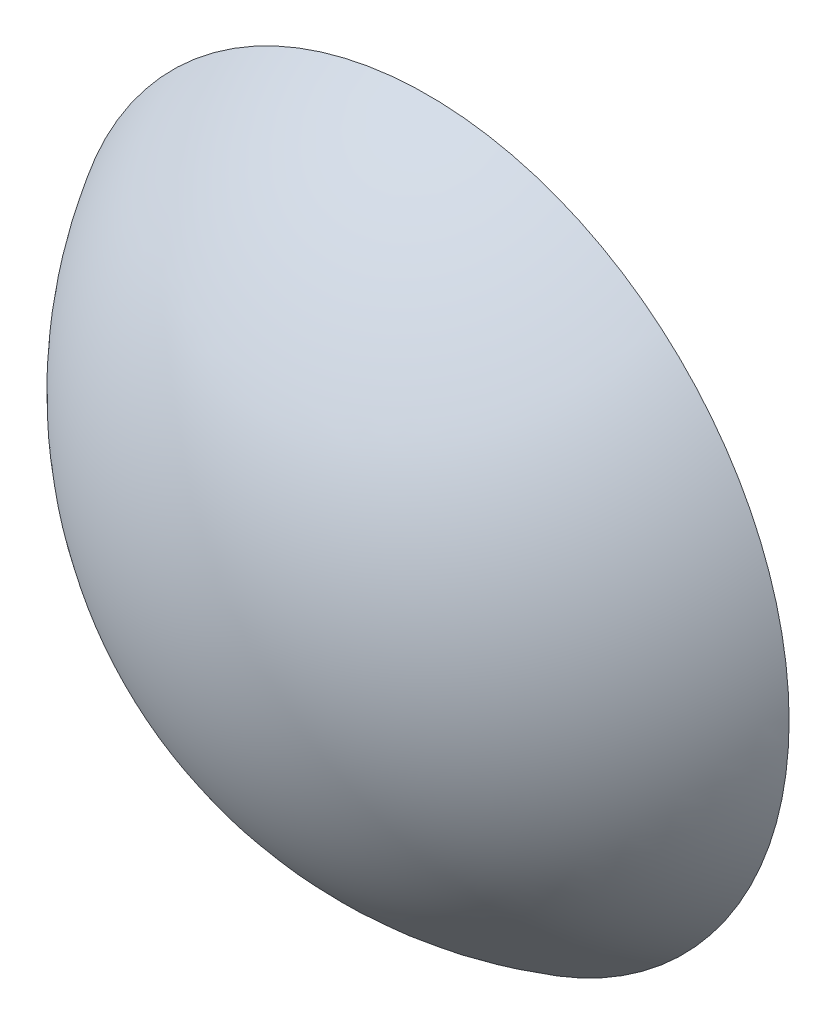
SolidWorks part; units mm, degrees
ref_plane "Front Plane" through (0, 0, 0) normal (0, 0, 1) x (1, 0, 0)
ref_plane "Top Plane" through (0, 0, 0) normal (0, 1, 0) x (1, 0, 0)
ref_plane "Right Plane" through (0, 0, 0) normal (1, 0, 0) x (0, 0, -1)
ref_plane "plane:profile-xz" through (0, 0, 0) normal (0, -1, 0) x (1, 0, 0)
sketch "sketch:main-profile" plane through (0, 0, 0) normal (0, -1, 0) x (1, 0, 0)
  line L0 (0, 10) -> (0, 5)
  line L1 (0, 5) -> (8.6603, 5)
  line L2 (0, -15) -> (0, 15) construction
  arc A0 (8.6603, 5) -> (0, 10) centre (0, 0) ccw
revolve "feature:sphere-cap" add sketch "sketch:main-profile" angle 360 about L2
